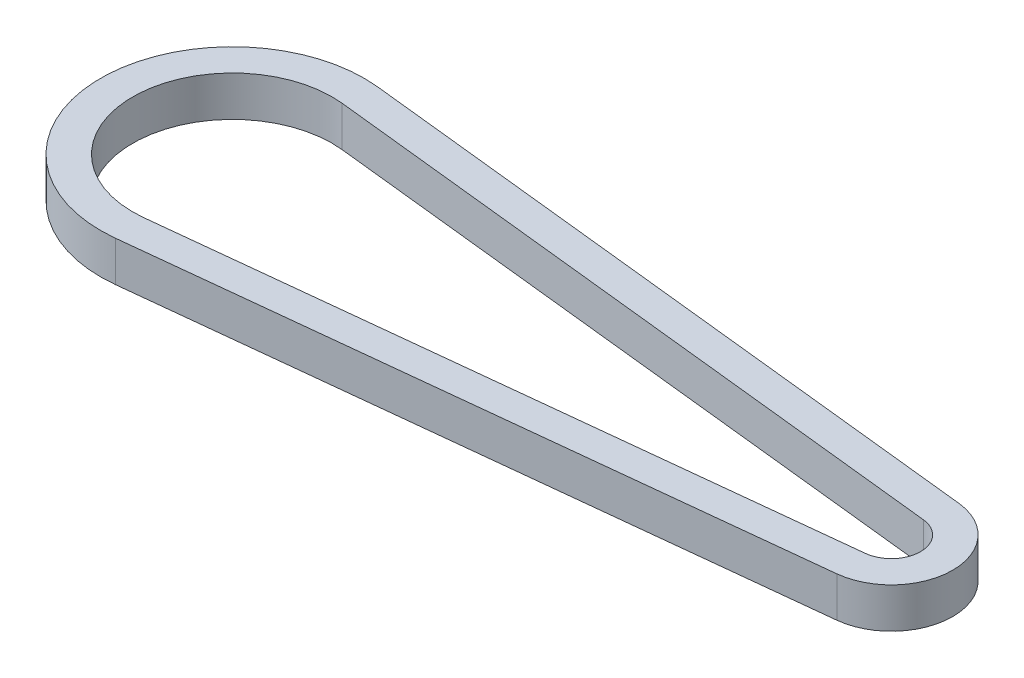
SolidWorks part; units mm, degrees
ref_plane "Front Plane" through (0, 0, 0) normal (0, 0, 1) x (1, 0, 0)
ref_plane "Top Plane" through (0, 0, 0) normal (0, 1, 0) x (1, 0, 0)
ref_plane "Right Plane" through (0, 0, 0) normal (1, 0, 0) x (0, 0, -1)
sketch "Sketch1" plane through (0, 0, 0) normal (0, 1, 0) x (1, 0, 0)
  line L0 (3.3147, 30.8223) -> (205.8721, 9.0388)
  line L2 (205.8721, -9.0388) -> (3.3147, -30.8223)
  arc A0 (3.3147, 30.8223) -> (3.3147, -30.8223) centre (0, 0) ccw
  arc A1 (205.8721, -9.0388) -> (205.8721, 9.0388) centre (204.9, 0) ccw
  dimension "D1" = 9.0909
  dimension "D2" = 31
  dimension "D3" = 204.9
extrude "Extrude-Thin1" add sketch "Sketch1" along normal blind 12.5 thin thin type one direction wall 10
move or copy body "Body-Move/Copy1" [suppressed] bodies to move or copy 101
equation "\"12.5mmm\"=10"
